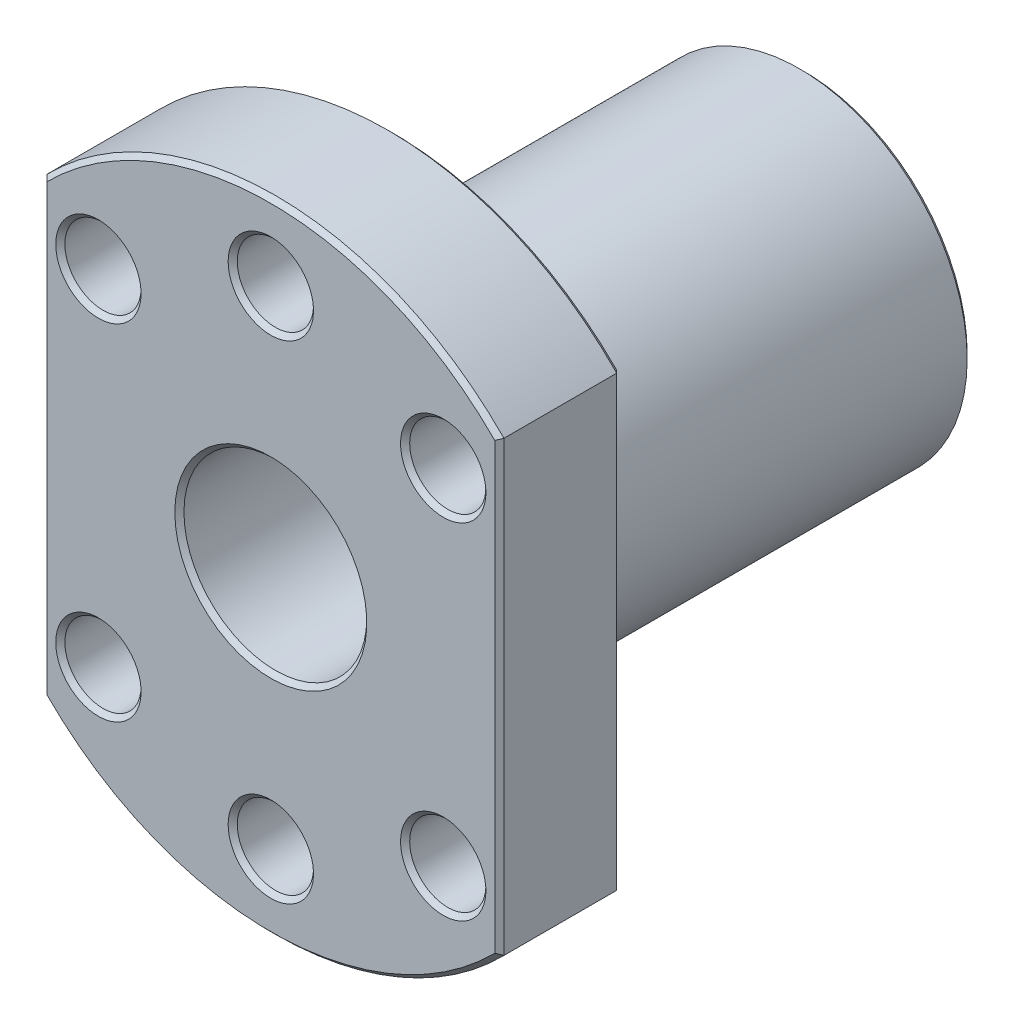
SolidWorks part; units mm, degrees
material "Plain Carbon Steel"
ref_plane "Front Plane" through (0, 0, 0) normal (0, 0, 1) x (1, 0, 0)
ref_plane "Top Plane" through (0, 0, 0) normal (0, 1, 0) x (1, 0, 0)
ref_plane "Right Plane" through (0, 0, 0) normal (1, 0, 0) x (0, 0, -1)
sketch "Sketch1" plane through (0, 0, 0) normal (1, 0, 0) x (0, 0, -1)
  line L0 (-27, 0) -> (-1.1455, 0) construction
  line L1 (17.5, 6) -> (-17.5, 6)
  line L2 (-17.5, 6) -> (-17.5, 21)
  line L3 (-17.5, 21) -> (-9.5, 21)
  line L4 (-9.5, 21) -> (-9.5, 11)
  line L5 (-9.5, 11) -> (17.5, 11)
  line L6 (17.5, 11) -> (17.5, 6)
  line L7 (0, 6) -> (0, 0) construction
  dimension "D1" = 27
  dimension "D2" = 8
  dimension "D3" = 21
  dimension "D4" = 12
  dimension "D5" = 22
revolve "Revolve1" add sketch "Sketch1" angle 360 about L0
sketch "Sketch2" plane through (0, 0, 0) normal (0, 1, 0) x (1, 0, 0)
  line L0 (-21, -17.5) -> (21, -17.5) construction
  line L1 (-21, -9.5) -> (-15, -9.5)
  line L2 (-21, -9.5) -> (-21, -17.5)
  line L3 (-21, -17.5) -> (-15, -17.5)
  line L4 (-15, -9.5) -> (-15, -17.5)
  line L6 (21, -9.5) -> (15, -9.5)
  line L7 (21, -9.5) -> (21, -17.5)
  line L8 (21, -17.5) -> (15, -17.5)
  line L9 (15, -9.5) -> (15, -17.5)
  dimension "D1" = 30
extrude "Cut-Extrude1" cut sketch "Sketch2" against normal through all both and the other way through all
sketch "Sketch3" plane through (0, 0, 17.5) normal (0, 0, 1) x (1, 0, 0)
  line L0 (0, 16) -> (0, 0) construction
  circle A0 centre (0, 16) radius 2.5
  circle A1 centre (11.3137, 11.3137) radius 2.5
  circle A2 centre (16, 0) radius 2.5 construction
  circle A3 centre (11.3137, -11.3137) radius 2.5
  circle A4 centre (0, -16) radius 2.5
  circle A5 centre (-11.3137, -11.3137) radius 2.5
  circle A6 centre (-16, 0) radius 2.5 construction
  circle A7 centre (-11.3137, 11.3137) radius 2.5
  point P19 (0, 0)
  dimension "D2" = 5
  dimension "D1" = 16
  dimension "D3" = 8
extrude "Cut-Extrude2" cut sketch "Sketch3" against normal blind 10
chamfer "Chamfer1" distance 0.3 angle 45 24 edges at (11, 0, 9.5) (-15, 0, 9.5) (0, 21, 9.5) (0, -21, 9.5) (15, 0, 9.5) (2.5, 16, 9.5) (-8.8137, 11.3137, 9.5) (-8.8137, -11.3137, 9.5) (2.5, -16, 9.5) (13.8137, -11.3137, 9.5) (13.8137, 11.3137, 9.5) (-15, 0, 17.5) (0, -21, 17.5) (0, 21, 17.5) (15, 0, 17.5) (6, 0, 17.5) (2.5, 16, 17.5) (-8.8137, 11.3137, 17.5) (-8.8137, -11.3137, 17.5) (2.5, -16, 17.5) (13.8137, -11.3137, 17.5) (13.8137, 11.3137, 17.5) (6, 0, -17.5) (11, 0, -17.5)
sketch "Sketch4" [suppressed] plane through (0, 0, 0) normal (1, 0, 0) x (0, 0, -1)
  line L0 (0, 0) -> (0, 11) construction
  line L1 (22, 11) -> (12, 11)
  line L2 (-22, 11) -> (-22, 24)
  line L3 (-22, 24) -> (-12, 24)
  line L4 (-12, 24) -> (-12, 14)
  line L5 (-12, 14) -> (22, 14)
  line L6 (22, 14) -> (22, 11)
  line L7 (-17.9283, 0) -> (16.6653, 0) construction
  line L8 (-12, 11) -> (-22, 11)
  line L9 (-12, 11) -> (12, 11) construction
  line L10 (-12, 11) -> (-12, 8)
  line L11 (-12, 8) -> (12, 8)
  line L12 (12, 11) -> (12, 8)
  dimension "D1" = 24
  dimension "D2" = 28
  dimension "D3" = 10
  dimension "D4" = 34
  dimension "D5" = 22
  dimension "D6" = 22
  dimension "D7" = 8
  dimension "D8" = 10
revolve "Revolve2" [suppressed] add sketch "Sketch4" angle 360 about L7
sketch "Sketch5" [suppressed] plane through (0, 0, 22) normal (0, 0, 1) x (1, 0, 0)
  line L0 (0, 35.9904) -> (0, 19.305) construction
  line L1 (-28.3026, 0) -> (22.4371, 0) construction
  line L2 (20, 20) -> (-20, 20)
  line L3 (20, 20) -> (20, 30)
  line L4 (20, 30) -> (-20, 30)
  line L5 (-20, 20) -> (-20, 30)
  line L6 (20, 20) -> (-20, 30) construction
  line L7 (20, 30) -> (-20, 20) construction
  line L8 (20, -20) -> (20, -30)
  line L9 (20, -20) -> (-20, -20)
  line L10 (-20, -20) -> (-20, -30)
  line L11 (20, -30) -> (-20, -30)
  point P1 (0, 25)
  dimension "D1" = 40
  dimension "D2" = 20
  dimension "D3" = 10
extrude "Cut-Extrude3" [suppressed] cut sketch "Sketch5" against normal through all
sketch "Sketch6" [suppressed] plane through (0, 0, 22) normal (0, 0, 1) x (1, 0, 0)
  line L0 (0, 0) -> (-19, 0) construction
  circle A0 centre (-19, 0) radius 2.75
  circle A1 centre (-13.435, 13.435) radius 2.75
  circle A2 centre (0, 19) radius 2.75 construction
  circle A3 centre (13.435, 13.435) radius 2.75
  circle A4 centre (19, 0) radius 2.75
  circle A5 centre (13.435, -13.435) radius 2.75
  circle A6 centre (0, -19) radius 2.75 construction
  circle A7 centre (-13.435, -13.435) radius 2.75
  point P20 (0, 0)
  dimension "D1" = 5.5
  dimension "D2" = 19
  dimension "D3" = 8
extrude "Cut-Extrude4" [suppressed] cut sketch "Sketch6" against normal through all
sketch "Sketch7" [suppressed] plane through (0, 20, 0) normal (0, 1, 0) x (1, 0, 0)
  line L0 (0, 0) -> (0, -18) construction
  line L1 (0, 0) -> (-14, 0) construction
  line L2 (-14, 22) -> (-14, -12) construction
  circle A0 centre (0, -18) radius 1.5
  circle A1 centre (0, 18) radius 1.5
  dimension "D1" = 3
  dimension "D2" = 18
extrude "Cut-Extrude5" [suppressed] cut sketch "Sketch7" against normal through all
ref_plane "Plane1" [suppressed] through (13.6768, 5.6651, 0) normal (0.9239, 0.3827, 0) x (0, 0, -1)
sketch "Sketch8" [suppressed] plane through (13.6768, 5.6651, 0) normal (0.9239, 0.3827, 0) x (0, 0, -1)
  line L0 (-12, 0) -> (-22, 0) construction
  line L2 (0, 0) -> (-17, 0) construction
  line L3 (-22, 13.4007) -> (-22, -23.5545) construction
  line L4 (-12, -14) -> (-12, 14) construction
  circle A0 centre (-17, 0) radius 2.5
  dimension "D1" = 5
extrude "Cut-Extrude6" [suppressed] cut sketch "Sketch8" against normal blind 10 and the other way through all
sketch "Sketch9" [suppressed] plane through (13.6768, 5.6651, 0) normal (0.9239, 0.3827, 0) x (0, 0, -1)
  circle A0 centre (-17, 0) radius 3
  dimension "D1" = 6
extrude "Cut-Extrude7" [suppressed] cut sketch "Sketch9" along normal through all
chamfer "Chamfer2" [suppressed] distance 0.5 angle 45
other "DeleteFace1" [suppressed]
